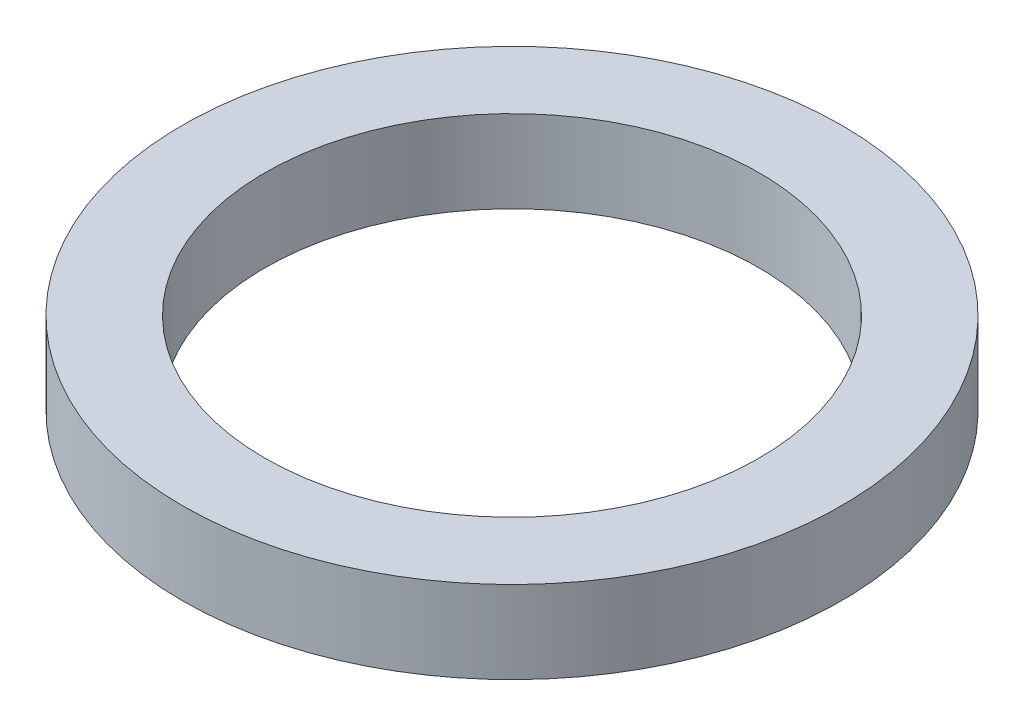
SolidWorks part; units mm, degrees
ref_plane "Front Plane" through (0, 0, 0) normal (0, 0, 1) x (1, 0, 0)
ref_plane "Top Plane" through (0, 0, 0) normal (0, 1, 0) x (1, 0, 0)
ref_plane "Right Plane" through (0, 0, 0) normal (1, 0, 0) x (0, 0, -1)
sketch "Sketch1" plane through (0, 0, 0) normal (0, 1, 0) x (1, 0, 0)
  circle A0 centre (0, 0) radius 4
  circle A1 centre (0, 0) radius 3
  dimension "D1" = 8
  dimension "D2" = 6
extrude "Boss-Extrude1" add sketch "Sketch1" along normal blind 1
equation "\"N_pin\"= 24"
equation "\"R_pin\"= 60"
equation "\"d_pin\"= 13"
equation "\"e\"= 1.5"
equation "\"t_disk\"= 5"
equation "\"N_outpin\"= 8"
equation "\"R_outpin\"= 34"
equation "\"d_outpin\"= 13"
equation "\"N_lobes\"= \"N_pin\" - 1"
equation "\"d_outhole\"= \"d_outpin\" + 2 * \"e\""
equation "\"ratio\"= \"N_lobes\""
equation "\"d_center\"= 24"
equation "\"a_hole1\"= 0 / \"N_lobes\""
equation "\"a_hole2\"= 360 / \"N_disk\" / \"N_lobes\""
equation "\"a_hole3\"= 720 / \"N_disk\" / \"N_lobes\""
equation "\"N_disk\"= 3"
equation "\"t_gap\"= 1"
equation "\"L_stack\"= \"N_disk\" * \"t_disk\" + (\"N_disk\" - 1) * \"t_gap\""
equation "\"d_pinshaft\"= 6"
equation "\"d_ecc\"= 15"
equation "\"d_outbrg\"= 47"
equation "\"w_outbrg\"= 7"
equation "\"d_outshaft\"= 35"
equation "\"w_brg\"= 5"
equation "\"c_run\"= 0.5"
equation "\"c_ax\"= \"t_gap\""
equation "\"D_pocket\"= 2 * \"R_pin\" + \"d_pin\" + 2 * \"c_run\""
equation "\"h_pocket\"= \"L_stack\" + 2 * \"c_ax\""
equation "\"t_floor\"= 8"
equation "\"d_insert\"= 5.6"
equation "\"N_bolt\"= 8"
equation "\"R_bolt\"= \"D_pocket\" / 2 + 2 + \"d_insert\" / 2"
equation "\"D_housing\"= 2 * (\"R_bolt\" + \"d_insert\" / 2 + 2.5)"
equation "\"D1@Sketch1\"=\"d_pinshaft\"+2"
equation "\"D2@Sketch1\"=\"d_pinshaft\""
equation "\"D1@Boss-Extrude1\"=\"t_gap\""
